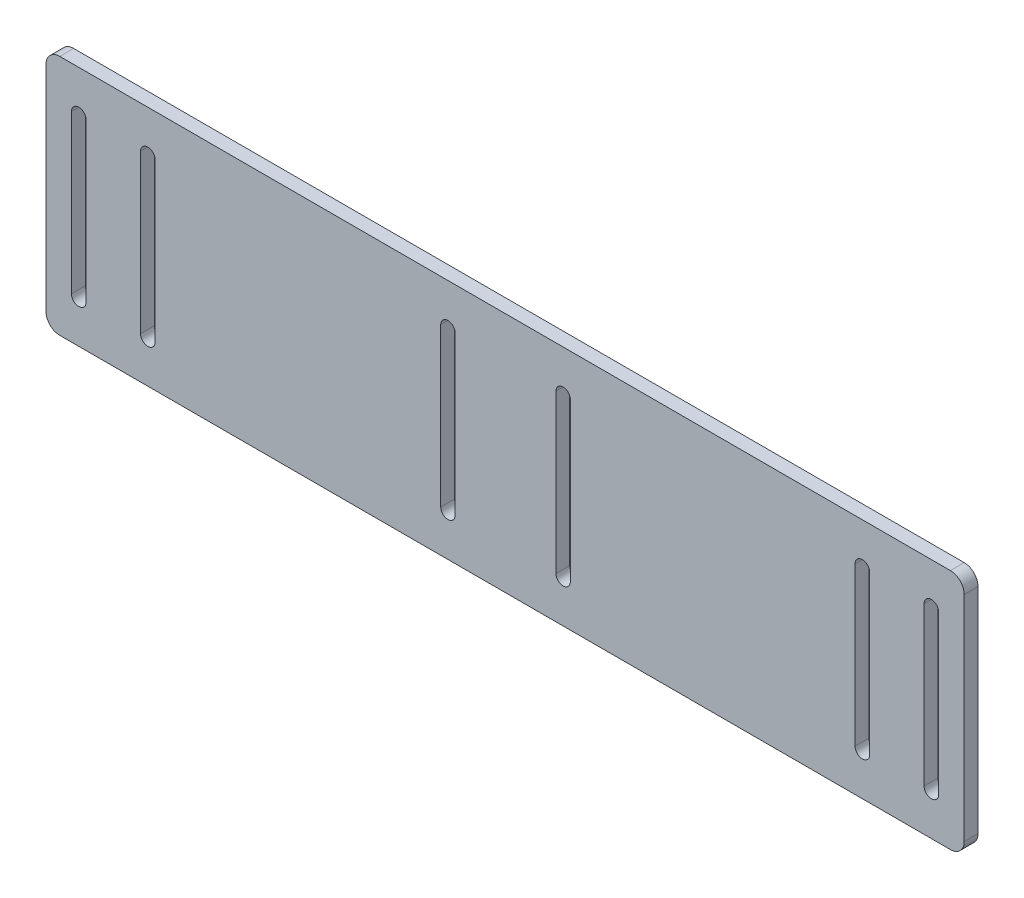
SolidWorks part; units mm, degrees
ref_plane "Front Plane" through (0, 0, 0) normal (0, 0, 1) x (1, 0, 0)
ref_plane "Top Plane" through (0, 0, 0) normal (0, 1, 0) x (1, 0, 0)
ref_plane "Right Plane" through (0, 0, 0) normal (1, 0, 0) x (0, 0, -1)
sketch "Sketch2" plane through (0, 0, -1024.0857) normal (0, 0, 1) x (1, 0, 0)
  line L0 (-0.1188, 700) -> (-0.1188, 560) construction
  line L1 (-493.1188, 700) -> (-493.1188, 560)
  line L3 (-440.1188, 700) -> (-440.1188, 560) construction
  line L6 (-480.1188, 700) -> (-479.9788, 560) construction
  line L7 (38.8812, 700) -> (38.8812, 560) construction
  line L8 (-480.1188, 700) -> (-493.1188, 700)
  line L9 (-480.1188, 700) -> (38.8812, 700)
  line L10 (-480.1188, 700) -> (-480.1188, 560) construction
  line L11 (-480.1188, 560) -> (38.8812, 560)
  line L12 (38.8812, 700) -> (38.8812, 560)
  line L13 (-480.1188, 560) -> (-493.1188, 560)
  line L14 (-493.1188, 713) -> (-493.1188, 547) construction
  line L15 (-427.1188, 584.25) -> (-427.1188, 675.75) construction
  line L16 (-431.3688, 584.25) -> (-431.3688, 675.75) construction
  line L17 (-422.8688, 584.25) -> (-422.8688, 675.75) construction
  line L18 (15.6312, 700) -> (15.6312, 560) construction
  line L19 (24.1312, 700) -> (24.1312, 560) construction
  line L20 (-467.1188, 584.25) -> (-467.1188, 675.75) construction
  line L21 (-20.1188, 700) -> (-20.1188, 560) construction
  line L22 (-462.8688, 584.25) -> (-462.8688, 675.75) construction
  line L25 (-471.3688, 584.25) -> (-471.3688, 675.75) construction
  line L28 (-220.6188, 700) -> (-220.6188, 560) construction
  line L29 (-24.3688, 700) -> (-24.3688, 560) construction
  line L30 (-15.8688, 700) -> (-15.8688, 560) construction
  line L31 (24.1312, 700) -> (15.6312, 700)
  line L32 (19.8812, 700) -> (19.8812, 560) construction
  line L33 (19.8812, 584.25) -> (19.8812, 675.75) construction
  line L34 (15.6312, 584.25) -> (15.6312, 675.75)
  line L35 (24.1312, 584.25) -> (24.1312, 675.75)
  line L36 (-434.1188, 584.25) -> (-434.1188, 675.75) construction
  line L37 (19.8812, 580) -> (19.8812, 560) construction
  line L38 (-20.1188, 584.25) -> (-20.1188, 675.75) construction
  line L39 (-15.8688, 584.25) -> (-15.8688, 675.75)
  line L40 (-24.3688, 584.25) -> (-24.3688, 675.75)
  line L41 (-421.1188, 584.25) -> (-421.1188, 675.75) construction
  line L42 (-425.3688, 584.25) -> (-425.3688, 675.75) construction
  line L43 (-416.8688, 584.25) -> (-416.8688, 675.75) construction
  line L44 (-461.1188, 584.25) -> (-461.1188, 675.75) construction
  line L45 (-456.8688, 584.25) -> (-456.8688, 675.75) construction
  line L46 (-465.3688, 584.25) -> (-465.3688, 675.75) construction
  line L47 (-493.1188, 713) -> (51.8812, 713) construction
  line L48 (-493.1188, 547) -> (51.8812, 547) construction
  line L49 (51.8812, 713) -> (51.8812, 547) construction
  line L52 (-438.3688, 584.25) -> (-438.3688, 675.75)
  line L55 (-227.1188, 700) -> (-227.1188, 560) construction
  line L56 (-429.8688, 584.25) -> (-429.8688, 675.75)
  line L57 (-474.1188, 584.25) -> (-474.1188, 675.75) construction
  line L58 (-469.8688, 584.25) -> (-469.8688, 675.75)
  line L59 (-478.3688, 584.25) -> (-478.3688, 675.75)
  arc A4 (15.6312, 584.25) -> (24.1312, 584.25) centre (19.8812, 584.25) ccw
  arc A5 (24.1312, 675.75) -> (15.6312, 675.75) centre (19.8812, 675.75) ccw
  arc A6 (-15.8688, 584.25) -> (-24.3688, 584.25) centre (-20.1188, 584.25) cw
  arc A7 (-24.3688, 675.75) -> (-15.8688, 675.75) centre (-20.1188, 675.75) cw
  arc A8 (-425.3688, 584.25) -> (-416.8688, 584.25) centre (-421.1188, 584.25) ccw construction
  arc A9 (-416.8688, 675.75) -> (-425.3688, 675.75) centre (-421.1188, 675.75) ccw construction
  arc A10 (-456.8688, 584.25) -> (-465.3688, 584.25) centre (-461.1188, 584.25) cw construction
  arc A11 (-465.3688, 675.75) -> (-456.8688, 675.75) centre (-461.1188, 675.75) cw construction
  arc A12 (-431.3688, 584.25) -> (-422.8688, 584.25) centre (-427.1188, 584.25) ccw construction
  arc A13 (-422.8688, 675.75) -> (-431.3688, 675.75) centre (-427.1188, 675.75) ccw construction
  arc A14 (-462.8688, 584.25) -> (-471.3688, 584.25) centre (-467.1188, 584.25) cw construction
  arc A15 (-471.3688, 675.75) -> (-462.8688, 675.75) centre (-467.1188, 675.75) cw construction
  arc A20 (-438.3688, 584.25) -> (-429.8688, 584.25) centre (-434.1188, 584.25) ccw
  arc A21 (-429.8688, 675.75) -> (-438.3688, 675.75) centre (-434.1188, 675.75) ccw
  arc A22 (-469.8688, 584.25) -> (-478.3688, 584.25) centre (-474.1188, 584.25) cw
  arc A23 (-478.3688, 675.75) -> (-469.8688, 675.75) centre (-474.1188, 675.75) cw
  point P18 (-427.1188, 630)
  point P34 (19.8812, 700)
  point P39 (-20.1188, 675.25)
  point P40 (-20.1188, 574.75)
  point P41 (-20.1188, 574.75)
  point P42 (-20.1188, 560)
  point P43 (19.8812, 630)
  point P44 (-20.1188, 560)
  point P49 (19.8812, 680)
  point P50 (19.8812, 580)
  point P57 (-20.1188, 630)
  point P64 (-421.1188, 630)
  point P71 (-461.1188, 630)
  point P77 (-467.1188, 630)
  point P83 (-434.1188, 630)
  point P90 (-474.1188, 630)
  line M5 (-14.8688, 700) -> (-14.8688, -300)
  line M7 (14.6312, -300) -> (14.6312, 700)
  line M8 (14.6312, 700) -> (-14.8688, 700)
  dimension "D3" = 20
  dimension "D1" = 8.5
  dimension "D2" = 100
  dimension "D4" = 8.5
  dimension "D5" = 140
  dimension "D6" = 20
  dimension "D7" = 13
  dimension "D8" = 2
  dimension "D10" = 2
  dimension "D9" = 2
extrude "Boss-Extrude3" add sketch "Sketch2" along normal blind 8 contours L10 L11 L9 A9 L43 A8 L42 L40 A7 L39 A6 L46 A11 L45 A10 M5 | L11 M5 M7 M8 | L12 L9 L11 A5 L35 A4 L34 M7
fillet "Fillet1" radius 8 4 edges at (38.8812, 700, -1020.0857) (38.8812, 560, -1020.0857) (-493.1188, 560, -1020.0857) (-493.1188, 700, -1020.0857)
sketch "Sketch5" [suppressed] plane through (0, 0, -532.7708) normal (0, 0, 1) x (1, 0, 0)
  line L1 (-230.6188, 619.9) -> (-210.5188, 619.9)
  line L2 (-230.6188, 619.9) -> (-230.6188, 640)
  line L3 (-230.6188, 640) -> (-210.5188, 640)
  line L4 (-210.5188, 619.9) -> (-210.5188, 640)
  dimension "D1" = 20.1
  dimension "D2" = 20.1
extrude "Cut-Extrude1" [suppressed] cut sketch "Sketch5" against normal blind 2.5
sketch "Sketch6" [suppressed] plane through (0, 0, -560.7601) normal (0, 0, 1) x (1, 0, 0)
  line L0 (-191.0988, 632.575) -> (-202.5522, 632.575) construction
  line L1 (-202.5522, 627.425) -> (-191.0988, 627.425) construction
  line L2 (-250.1388, 627.425) -> (-238.6855, 627.425) construction
  line L3 (-238.6855, 632.575) -> (-250.1388, 632.575) construction
  line L4 (-191.0988, 632.575) -> (-202.5522, 632.575)
  line L5 (-202.5522, 627.425) -> (-191.0988, 627.425)
  line L6 (-250.1388, 627.425) -> (-238.6855, 627.425)
  line L7 (-238.6855, 632.575) -> (-250.1388, 632.575)
  arc A0 (-191.0988, 627.425) -> (-191.0988, 632.575) centre (-191.0988, 630) ccw construction
  arc A1 (-202.5522, 632.575) -> (-202.5522, 627.425) centre (-202.5522, 630) ccw construction
  arc A2 (-238.6855, 627.425) -> (-238.6855, 632.575) centre (-238.6855, 630) ccw construction
  arc A3 (-250.1388, 632.575) -> (-250.1388, 627.425) centre (-250.1388, 630) ccw construction
  arc A4 (-191.0988, 627.425) -> (-191.0988, 632.575) centre (-191.0988, 630) ccw
  arc A5 (-202.5522, 632.575) -> (-202.5522, 627.425) centre (-202.5522, 630) ccw
  arc A6 (-238.6855, 627.425) -> (-238.6855, 632.575) centre (-238.6855, 630) ccw
  arc A7 (-250.1388, 632.575) -> (-250.1388, 627.425) centre (-250.1388, 630) ccw
extrude "Cut-Extrude2" [suppressed] cut sketch "Sketch6" against normal blind 10
sketch "Sketch7" plane through (0, 0, -1016.0857) normal (0, 0, 1) x (1, 0, 0)
  line L0 (-415.1188, 680) -> (-190.3286, 680) construction
  line L1 (-415.1188, 580) -> (-184.7009, 580) construction
  line L2 (-419.3688, 675.75) -> (-190.3286, 675.75) construction
  line L3 (-419.3688, 584.25) -> (-184.7009, 584.25) construction
  line L4 (-244.8188, 617) -> (-244.8188, 644.2) construction
  line L5 (-244.8188, 617) -> (-244.8188, 644.2) construction
  line L6 (-187.2438, 675.75) -> (-187.2438, 584.25) construction
  line L7 (-253.9938, 700) -> (-253.9938, 560) construction
  line L8 (-191.4188, 675.75) -> (-191.4188, 584.25) construction
  line L9 (-183.0688, 675.75) -> (-183.0688, 584.25) construction
  line L12 (-485.1188, 560) -> (30.8812, 560) construction
  line L13 (-485.1188, 700) -> (30.8812, 700) construction
  line L14 (-485.1188, 560) -> (30.8812, 560) construction
  line L15 (-485.1188, 700) -> (30.8812, 700) construction
  line L16 (-247.8188, 617) -> (-247.8188, 644.2) construction
  line L17 (-223.6188, 630) -> (-223.6188, 711.2377) construction
  line L18 (-256.9938, 675.75) -> (-256.9938, 584.25) construction
  line L19 (-220.6188, 630) -> (-220.6188, 711.2377) construction
  line L20 (-253.9938, 675.75) -> (-253.9938, 584.25) construction
  line L21 (-249.8188, 675.75) -> (-249.8188, 584.25) construction
  line L22 (-258.1688, 675.75) -> (-258.1688, 584.25) construction
  line L23 (-252.8188, 675.75) -> (-252.8188, 584.25) construction
  line L24 (-261.1688, 675.75) -> (-261.1688, 584.25) construction
  line L25 (-190.2438, 675.75) -> (-190.2438, 584.25) construction
  line L26 (-194.4188, 675.75) -> (-194.4188, 584.25) construction
  line L27 (-186.0688, 675.75) -> (-186.0688, 584.25) construction
  line L28 (-226.8688, 630) -> (-226.8688, 711.2377) construction
  line L29 (-260.2438, 675.75) -> (-260.2438, 584.25) construction
  line L30 (-256.0688, 675.75) -> (-256.0688, 584.25)
  line L31 (-264.4188, 675.75) -> (-264.4188, 584.25)
  line L32 (-193.4938, 675.75) -> (-193.4938, 584.25) construction
  line L33 (-197.6688, 675.75) -> (-197.6688, 584.25)
  line L34 (-189.3188, 675.75) -> (-189.3188, 584.25)
  arc A0 (-410.8688, 675.75) -> (-419.3688, 675.75) centre (-415.1188, 675.75) ccw construction
  arc A1 (-419.3688, 584.25) -> (-410.8688, 584.25) centre (-415.1188, 584.25) ccw construction
  arc A2 (-249.8188, 675.75) -> (-258.1688, 675.75) centre (-253.9938, 675.75) ccw construction
  arc A3 (-258.1688, 584.25) -> (-249.8188, 584.25) centre (-253.9938, 584.25) ccw construction
  arc A4 (-191.4188, 675.75) -> (-183.0688, 675.75) centre (-187.2438, 675.75) cw construction
  arc A5 (-183.0688, 584.25) -> (-191.4188, 584.25) centre (-187.2438, 584.25) cw construction
  arc A6 (-252.8188, 675.75) -> (-261.1688, 675.75) centre (-256.9938, 675.75) ccw construction
  arc A7 (-261.1688, 584.25) -> (-252.8188, 584.25) centre (-256.9938, 584.25) ccw construction
  arc A8 (-194.4188, 675.75) -> (-186.0688, 675.75) centre (-190.2438, 675.75) cw construction
  arc A9 (-186.0688, 584.25) -> (-194.4188, 584.25) centre (-190.2438, 584.25) cw construction
  arc A10 (-256.0688, 675.75) -> (-264.4188, 675.75) centre (-260.2438, 675.75) ccw
  arc A11 (-264.4188, 584.25) -> (-256.0688, 584.25) centre (-260.2438, 584.25) ccw
  arc A12 (-197.6688, 675.75) -> (-189.3188, 675.75) centre (-193.4938, 675.75) cw
  arc A13 (-189.3188, 584.25) -> (-197.6688, 584.25) centre (-193.4938, 584.25) cw
  point P8 (-187.2438, 630)
  point P36 (-253.9938, 675.75)
  point P37 (-253.9938, 584.25)
  point P40 (-253.9938, 630)
  point P53 (-190.2438, 630)
  point P60 (-256.9938, 675.75)
  point P61 (-256.9938, 584.25)
  point P64 (-256.9938, 630)
  point P69 (-193.4938, 630)
  point P76 (-260.2438, 630)
  dimension "D2" = 2
  dimension "D3" = 2
  dimension "D4" = 8.35
  dimension "D1" = 5
  dimension "D5" = 2
  dimension "D6" = 3.25
extrude "Cut-Extrude3" cut sketch "Sketch7" against normal blind 10
equation "\"2.5.00mm\"=10"
